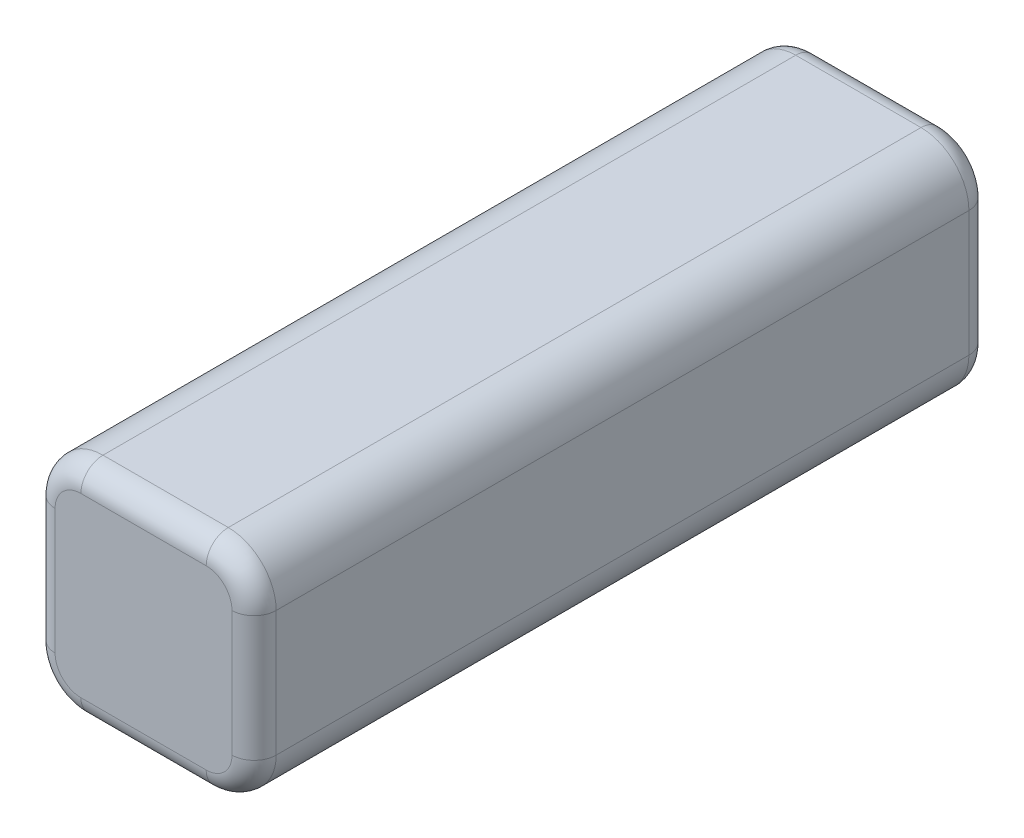
SolidWorks part; units mm, degrees
ref_plane "Plano frontal" through (0, 0, 0) normal (0, 0, 1) x (1, 0, 0)
ref_plane "Plano superior" through (0, 0, 0) normal (0, 1, 0) x (1, 0, 0)
ref_plane "Plano direito" through (0, 0, 0) normal (1, 0, 0) x (0, 0, -1)
sketch "Esboço1" plane through (0, 0, 0) normal (0, 0, 1) x (1, 0, 0)
  line L4 (-0.85, 1.5) -> (0.85, 1.5)
  line L5 (1.5, -0.85) -> (1.5, 0.85)
  line L6 (0, 0) -> (1.4157, -1.4157) construction
  line L7 (-0.85, -1.5) -> (0.85, -1.5)
  line L8 (-1.5, -0.85) -> (-1.5, 0.85)
  arc A4 (-1.5, 0.85) -> (-0.85, 1.5) centre (-0.85, 0.85) cw
  arc A5 (0.85, 1.5) -> (1.5, 0.85) centre (0.85, 0.85) cw
  arc A6 (0.85, -1.5) -> (1.5, -0.85) centre (0.85, -0.85) ccw
  arc A7 (-0.85, -1.5) -> (-1.5, -0.85) centre (-0.85, -0.85) cw
extrude "Ressalto-extrusão1" add sketch "Esboço1" along normal blind 10
fillet "Filete1" radius 0.3 16 edges at (-1.5, 0, 0) (-1.3096, -1.3096, 0) (0, -1.5, 0) (1.3096, -1.3096, 0) (1.5, 0, 0) (1.3096, 1.3096, 0) (0, 1.5, 0) (-1.3096, 1.3096, 0) (0, 1.5, 10) (1.3096, 1.3096, 10) (1.5, 0, 10) (1.3096, -1.3096, 10) (0, -1.5, 10) (-1.3096, -1.3096, 10) (-1.5, 0, 10) (-1.3096, 1.3096, 10)
sketch "Esboço2" plane through (0, 0, 0) normal (0, 0, -1) x (-1, 0, 0)
  line L0 (-1.5, 0) -> (1.5, 0) construction
  line L1 (-1.5, -0.85) -> (-1.5, 0.85) construction
  line L2 (1.5, 0.85) -> (1.5, -0.85) construction
  line L4 (-0.85, 1.5) -> (0.85, 1.5) construction
  line L5 (0, 1.5) -> (0, -1.5) construction
  line L6 (0.85, -1.5) -> (-0.85, -1.5) construction
